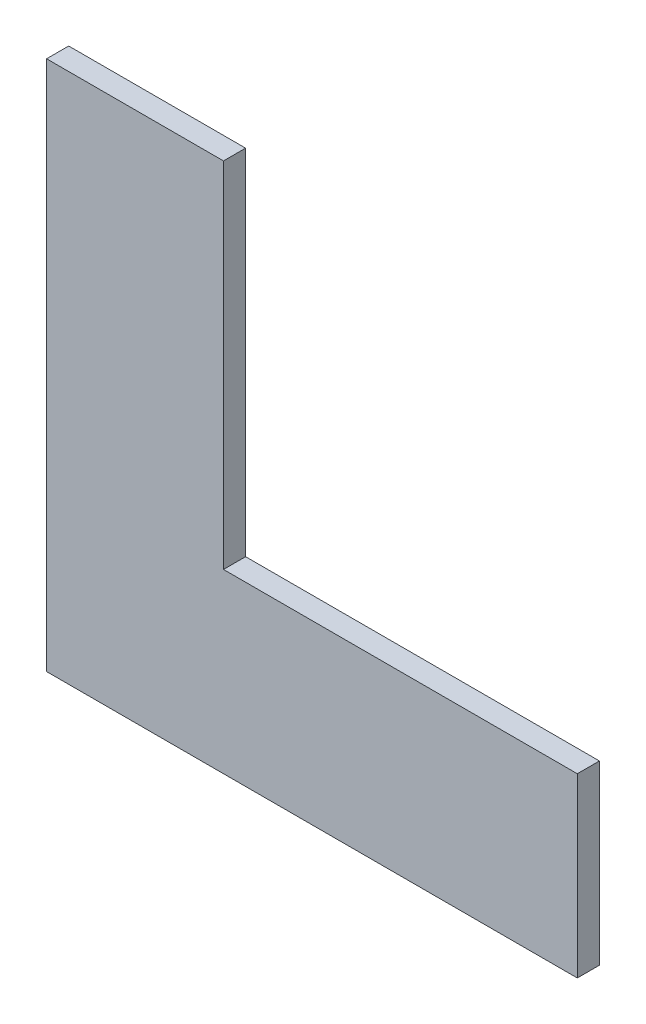
SolidWorks part; units mm, degrees
ref_plane "Front Plane" through (0, 0, 0) normal (0, 0, 1) x (1, 0, 0)
ref_plane "Top Plane" through (0, 0, 0) normal (0, 1, 0) x (1, 0, 0)
ref_plane "Right Plane" through (0, 0, 0) normal (1, 0, 0) x (0, 0, -1)
sketch "Sketch1" plane through (0, 0, 0) normal (0, 0, 1) x (1, 0, 0)
  line L0 (-38.1, 38.1) -> (-38.1, -38.1) construction
  line L1 (-38.1, -38.1) -> (38.1, -38.1) construction
  line L2 (38.1, -38.1) -> (38.1, -12.7) construction
  line L3 (38.1, -12.7) -> (-12.7, -12.7) construction
  line L4 (-12.7, -12.7) -> (-12.7, 38.1) construction
  line L5 (-12.7, 38.1) -> (-38.1, 38.1) construction
  line L6 (-38.1, -38.1) -> (38.1, 38.1) construction
  line L9 (-75.3773, -30.8003) -> (-70.9267, -26.3497) construction
  circle A0 centre (-73.152, -28.575) radius 2.2479 construction
  point P10 (-22.225, -22.352)
  point P11 (-28.575, 28.448)
  point P12 (-73.152, -28.575)
  point P13 (28.448, -28.575)
  point P15 (-22.352, -22.225)
  point P16 (-28.575, -73.152)
  dimension "Hole Size" = 4.4958
  dimension "Length (A)" = 76.2
  dimension "Length (C)" = 76.2
  dimension "Length (B)" = 25.4
  dimension "Hole Offset (A)" = 9.652
  dimension "Hole Offset (C)" = 9.652
  dimension "D1" = 45
  dimension "C'Sink Size" = 6.2941
  dimension "Hole Spacing (A)" = 50.8
  dimension "D3" = 50.8
  dimension "Hole Spacing (B)" = 6.35
  dimension "D4" = 9.525
  dimension "D5" = 9.525
  dimension "D6" = 6.35
  dimension "Hole Spacing (C)" = 50.8
  dimension "D2" = 50.8
sketch "Sketch2" plane through (0, 0, 0) normal (1, 0, 0) x (0, 0, -1)
  line L0 (1.016, 38.1) -> (-1.016, 38.1)
  dimension "Thickness" = 2.032
sketch "Sketch3" plane through (0, 0, 0) normal (0, 0, 1) x (1, 0, 0)
  line L0 (-38.1, 38.1) -> (-12.7, 38.1)
  line L1 (-12.7, 38.1) -> (-12.7, -12.7)
  line L2 (-12.7, -12.7) -> (38.1, -12.7)
  line L3 (38.1, -12.7) -> (38.1, -38.1)
  line L4 (38.1, -38.1) -> (-38.1, -38.1)
  line L5 (-38.1, -38.1) -> (-38.1, 38.1)
extrude "Boss-Extrude1" add sketch "Sketch3" along normal blind 3.175
equation "\"C'Sink Size@Sketch1\"=1.4 * \"Hole Size@Sketch1\""
equation "\"D3@Sketch1\"=\"Hole Spacing (A)@Sketch1\""
equation "\"D4@Sketch1\"=(\"Length (B)@Sketch1\"-\"Hole Spacing (B)@Sketch1\")/2"
equation "\"D5@Sketch1\"=\"D4@Sketch1\""
equation "\"D6@Sketch1\"=\"Hole Spacing (B)@Sketch1\""
equation "\"D2@Sketch1\"=\"Hole Spacing (C)@Sketch1\""
